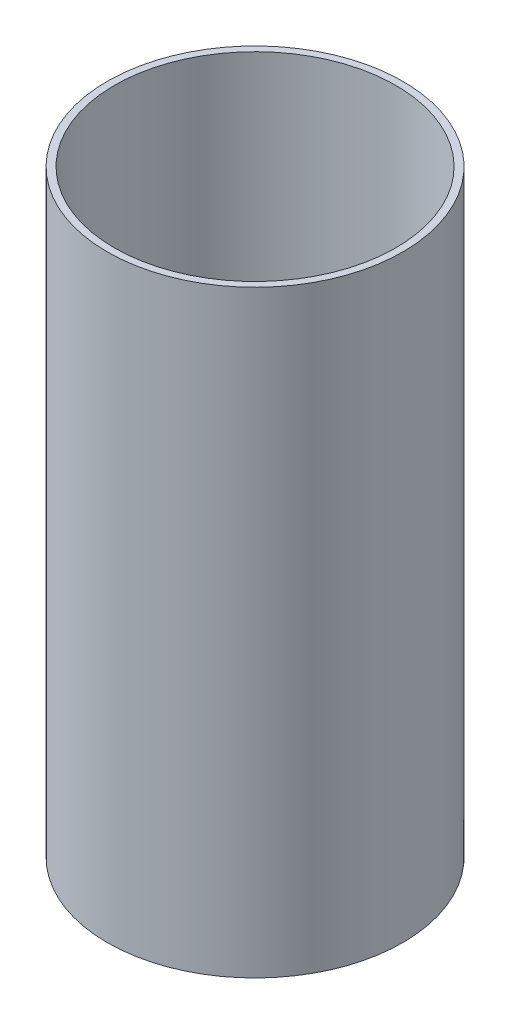
SolidWorks part; units mm, degrees
ref_plane "Front Plane" through (0, 0, 0) normal (0, 0, 1) x (1, 0, 0)
ref_plane "Top Plane" through (0, 0, 0) normal (0, 1, 0) x (1, 0, 0)
ref_plane "Right Plane" through (0, 0, 0) normal (1, 0, 0) x (0, 0, -1)
sketch "Sketch1" plane through (0, 0, 0) normal (0, 1, 0) x (1, 0, 0)
  circle A0 centre (0, 0) radius 21
  circle A1 centre (0, 0) radius 20
  dimension "D1" = 42
  dimension "D2" = 1
extrude "Boss-Extrude1" add sketch "Sketch1" along normal blind 85
